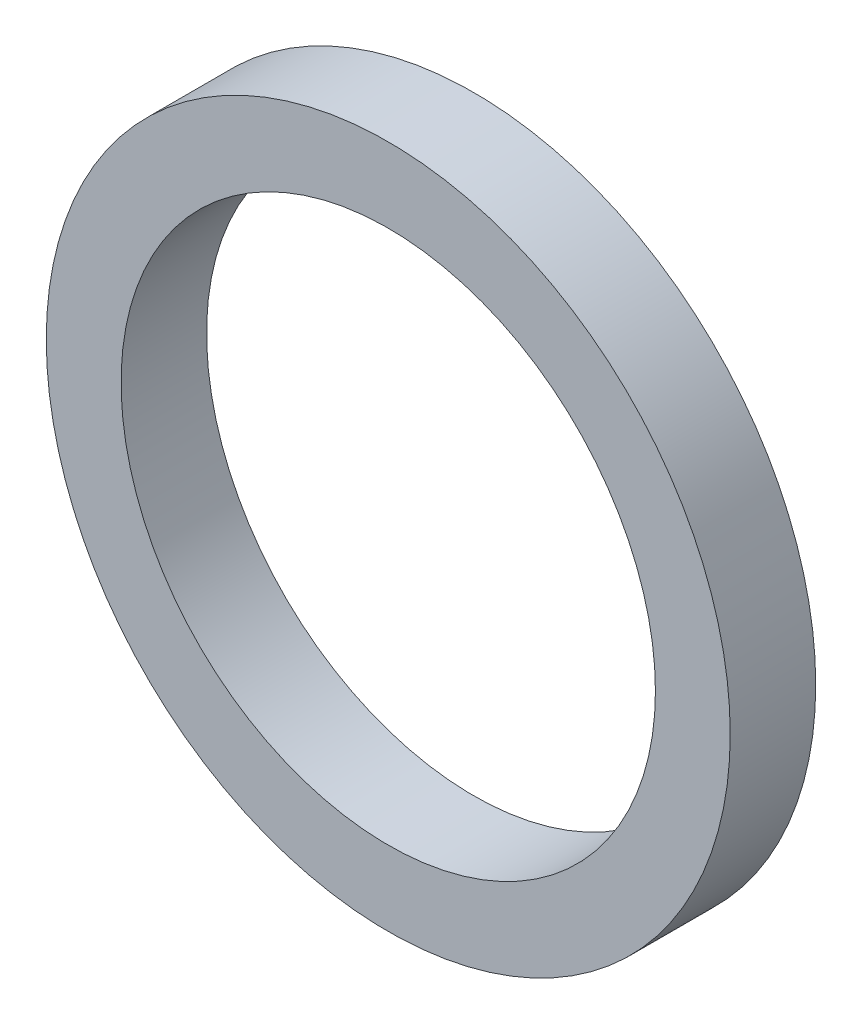
SolidWorks part; units mm, degrees
material "Chrome Stainless Steel"
ref_plane "Front Plane" through (0, 0, 0) normal (0, 0, 1) x (1, 0, 0)
ref_plane "Top Plane" through (0, 0, 0) normal (0, 1, 0) x (1, 0, 0)
ref_plane "Right Plane" through (0, 0, 0) normal (1, 0, 0) x (0, 0, -1)
sketch "Sketch1" plane through (0, 0, 0) normal (0, 0, 1) x (1, 0, 0)
  circle A0 centre (0, 0) radius 12.5
  circle A1 centre (0, 0) radius 16
  dimension "D1" = 25
  dimension "D2" = 32
extrude "Boss-Extrude1" add sketch "Sketch1" along normal blind 4
